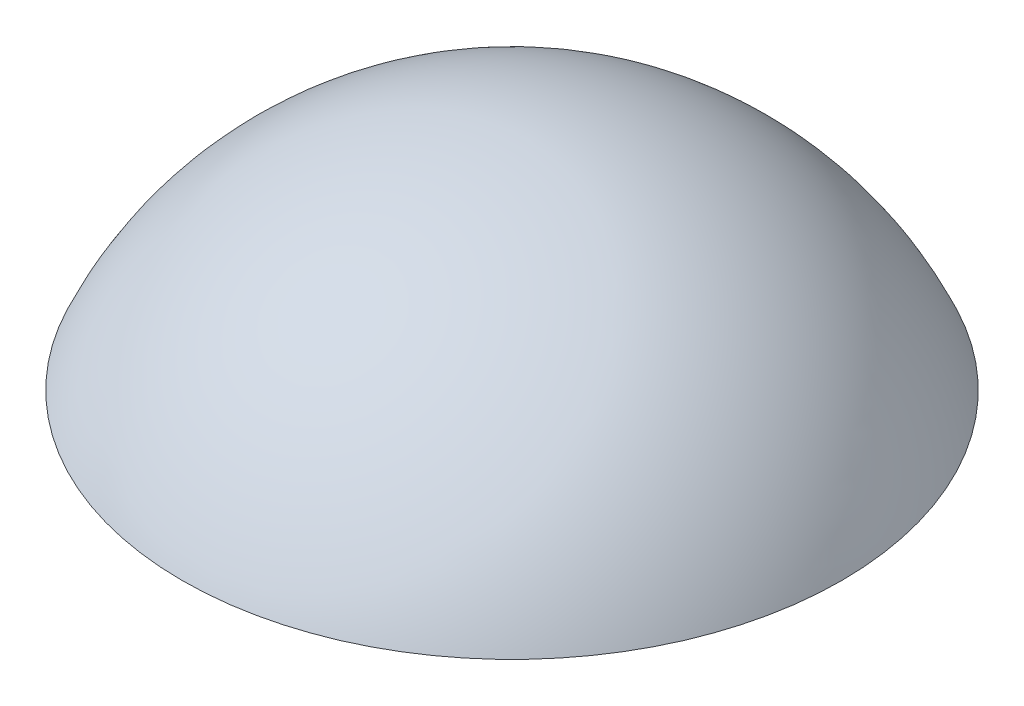
SolidWorks part; units mm, degrees
ref_plane "Front Plane" through (0, 0, 0) normal (0, 0, 1) x (1, 0, 0)
ref_plane "Top Plane" through (0, 0, 0) normal (0, 1, 0) x (1, 0, 0)
ref_plane "Right Plane" through (0, 0, 0) normal (1, 0, 0) x (0, 0, -1)
sketch "Sketch2" plane through (0, 0, 0) normal (0, 0, 1) x (1, 0, 0)
  line L0 (54.1727, -17.3572) -> (54.1727, 45.1268)
  line L1 (54.1727, -17.3572) -> (11.3929, -17.3572)
  line L2 (11.3929, -17.3572) -> (2.7002, -2.843)
  line L3 (2.7002, -2.843) -> (-18.8523, -2.843)
  arc A0 (-18.8523, -2.843) -> (54.1727, 45.1268) centre (53.9872, -34.1591) cw
  dimension "D1" = 73.025
  dimension "D2" = 62.484
revolve "Revolve2" add sketch "Sketch2" angle 360 about L0
sketch "Sketch4" plane through (0, 0, 0) normal (0, 0, 1) x (1, 0, 0)
  circle A0 centre (54.1727, -10.1214) radius 6.0118
  dimension "D1" = 73.025
extrude "Boss-Extrude1" add sketch "Sketch4" along normal blind 56.896
